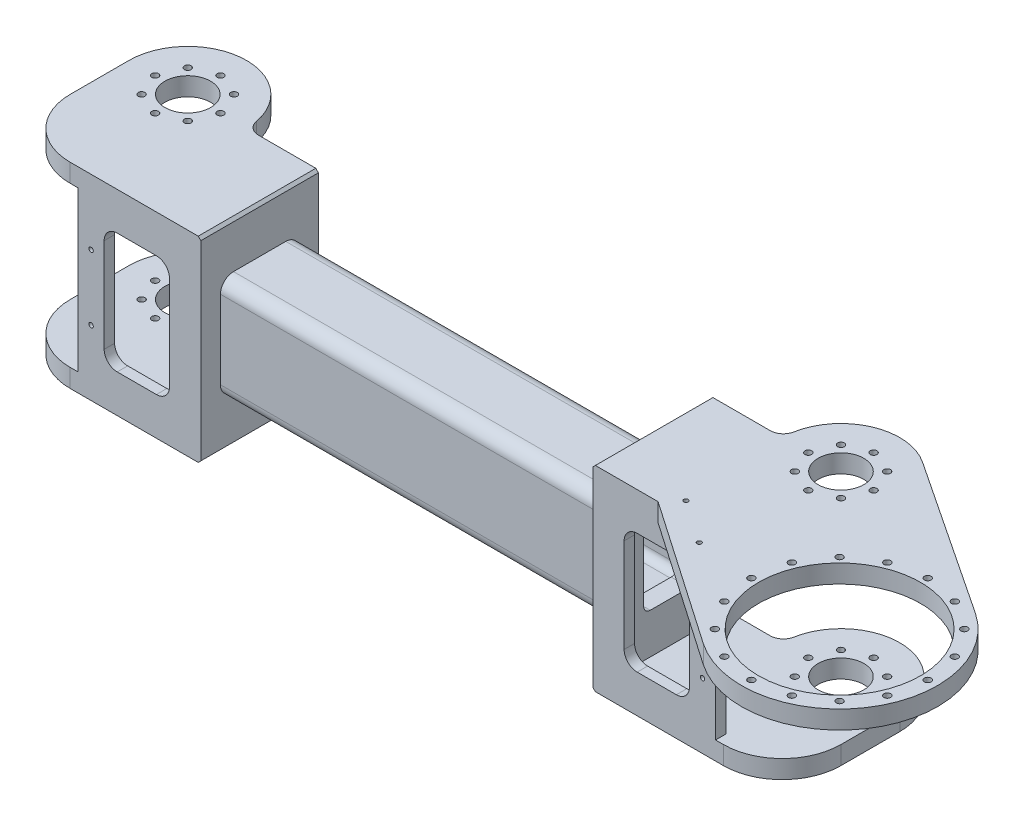
SolidWorks part; units mm, degrees
material "Q235"
ref_plane "Front" through (0, 0, 0) normal (0, 0, 1) x (1, 0, 0)
ref_plane "Top" through (0, 0, 0) normal (0, 1, 0) x (1, 0, 0)
ref_plane "Right" through (0, 0, 0) normal (1, 0, 0) x (0, 0, -1)
sketch "草图1" plane through (0, 0, 0) normal (0, 1, 0) x (1, 0, 0)
  line L0 (-45.9167, 45) -> (0, 45)
  line L1 (0, 45) -> (0, -45)
  line L2 (0, -45) -> (-100, -45)
  line L3 (-145, 0) -> (-145, 45)
  line L4 (0, 0) -> (-100, 0) construction
  line L5 (-100, 0) -> (-100, 45) construction
  arc A0 (-145, 45) -> (-55.7501, 53.1818) centre (-100, 45) cw
  arc A1 (-45.9167, 45) -> (-55.7501, 53.1818) centre (-45.9167, 55) cw
  arc A2 (-145, 0) -> (-100, -45) centre (-100, 0) ccw
  point P5 (0, 0)
  dimension "D2" = 100
  dimension "D5" = 10
  dimension "D6" = 45
  dimension "D1" = 90
  dimension "D3" = 45
  dimension "D4" = 145
extrude "凸台-拉伸1" add sketch "草图1" along normal mid plane 150
sketch "草图2" plane through (0, 0, 45) normal (0, 0, 1) x (1, 0, 0)
  line L1 (-314, 61) -> (-14, 61)
  line L2 (-314, 61) -> (-314, -61)
  line L3 (-314, -61) -> (-14, -61)
  line L4 (-14, 61) -> (-14, -61)
  line L6 (0, 75) -> (0, -75) construction
  point P4 (0, 0)
  dimension "D1" = 122
  dimension "D2" = 61
  dimension "D3" = 14
  dimension "D4" = 300
extrude "切除-拉伸1" cut sketch "草图2" against normal blind 200
sketch "草图3" plane through (0, 75, 0) normal (0, 1, 0) x (1, 0, 0)
  line L0 (0, 0) -> (-100, 0) construction
  line L1 (0, -45) -> (0, 45) construction
  line L2 (-100, 0) -> (-100, 45) construction
  circle A0 centre (-100, 45) radius 17.5
  dimension "D1" = 35
  dimension "D2" = 100
  dimension "D3" = 45
extrude "切除-拉伸2" cut sketch "草图3" against normal blind 240
sketch "草图4" plane through (0, -75, 0) normal (0, -1, 0) x (1, 0, 0)
  circle A0 centre (-100, -45) radius 25 construction
  circle A1 centre (-100, -20) radius 2.55
  circle A2 centre (-117.6777, -27.3223) radius 2.55
  circle A3 centre (-125, -45) radius 2.55
  circle A4 centre (-117.6777, -62.6777) radius 2.55
  circle A5 centre (-100, -70) radius 2.55
  circle A6 centre (-82.3223, -62.6777) radius 2.55
  circle A7 centre (-75, -45) radius 2.55
  circle A8 centre (-82.3223, -27.3223) radius 2.55
  point P22 (-100, -45)
  dimension "D1" = 50
  dimension "D2" = 5.1
  dimension "D3" = 8
extrude "切除-拉伸3" cut sketch "草图4" against normal blind 240
sketch "草图8" plane through (0, 0, 0) normal (0, 1, 0) x (1, 0, 0)
  line L0 (0, 0) -> (300, 0) construction
  line L1 (345.9167, 45) -> (300, 45)
  line L2 (300, 45) -> (300, -45)
  line L3 (300, -45) -> (400, -45)
  line L4 (300, 0) -> (400, 0) construction
  line L5 (400, 0) -> (506.066, -106.066) construction
  line L6 (445, 0) -> (445, 45)
  line L7 (400, 0) -> (400, 45) construction
  arc A0 (400, -45) -> (445, 0) centre (400, 0) ccw
  circle A1 centre (506.066, -106.066) radius 100 construction
  arc A2 (355.7501, 53.1818) -> (445, 45) centre (400, 45) cw
  arc A3 (355.7501, 53.1818) -> (345.9167, 45) centre (345.9167, 55) cw
  dimension "D1" = 90
  dimension "D5" = 200
  dimension "D7" = 45
  dimension "D8" = 10
  dimension "D2" = 300
  dimension "D3" = 100
  dimension "D4" = 150
  dimension "D6" = 135
extrude "凸台-拉伸4" add sketch "草图8" along normal mid plane 150 separate body
sketch "草图9" plane through (0, 0, 0) normal (1, 0, 0) x (0, 0, -1)
  line L0 (30, 40) -> (-30, -40) construction
  line L1 (-20, 40) -> (20, 40)
  line L2 (-30, 30) -> (-30, -30)
  line L3 (-20, -40) -> (20, -40)
  line L4 (30, 30) -> (30, -30)
  line L5 (0, 0) -> (-30, 0) construction
  line L6 (26, 30) -> (26, -30)
  line L7 (-20, -36) -> (20, -36)
  line L8 (-26, 30) -> (-26, -30)
  line L9 (-20, 36) -> (20, 36)
  arc A0 (20, 40) -> (30, 30) centre (20, 30) cw
  arc A1 (30, -30) -> (20, -40) centre (20, -30) cw
  arc A2 (-20, -40) -> (-30, -30) centre (-20, -30) cw
  arc A3 (-30, 30) -> (-20, 40) centre (-20, 30) cw
  arc A4 (26, -30) -> (20, -36) centre (20, -30) cw
  arc A5 (-20, -36) -> (-26, -30) centre (-20, -30) cw
  arc A6 (-26, 30) -> (-20, 36) centre (-20, 30) cw
  arc A7 (20, 36) -> (26, 30) centre (20, 30) cw
  dimension "D3" = 10
  dimension "D1" = 60
  dimension "D2" = 80
  dimension "D4" = 4
extrude "凸台-拉伸5" add sketch "草图9" along normal up to surface (300 mm away) up to face at (300, 0, 0)
sketch "草图10" plane through (0, 0, 45) normal (0, 0, 1) x (1, 0, 0)
  line L0 (300, 75) -> (300, -75) construction
  line L1 (314, 61) -> (514, 61)
  line L2 (314, 61) -> (314, -61)
  line L3 (314, -61) -> (514, -61)
  line L4 (514, 61) -> (514, -61)
  line L5 (0, 0) -> (381.7242, 0) construction
  dimension "D1" = 122
  dimension "D2" = 14
  dimension "D3" = 61
  dimension "D4" = 200
extrude "切除-拉伸4" cut sketch "草图10" against normal blind 200
sketch "草图11" plane through (0, 75, 0) normal (0, 1, 0) x (1, 0, 0)
  line L0 (300, 0) -> (400, 0) construction
  line L1 (300, 45) -> (300, -45) construction
  line L2 (400, 0) -> (400, 45) construction
  circle A0 centre (400, 45) radius 17.5
  dimension "D1" = 35
  dimension "D2" = 100
  dimension "D3" = 45
extrude "切除-拉伸5" cut sketch "草图11" against normal up to surface (150 mm away) up to face at (372.3141, -75, -18.2579)
sketch "草图12" plane through (0, 75, 0) normal (0, 1, 0) x (1, 0, 0)
  circle A0 centre (400, 45) radius 25 construction
  circle A1 centre (375, 45) radius 2.55
  circle A2 centre (382.3223, 27.3223) radius 2.55
  circle A3 centre (400, 20) radius 2.55
  circle A4 centre (417.6777, 27.3223) radius 2.55
  circle A5 centre (425, 45) radius 2.55
  circle A6 centre (417.6777, 62.6777) radius 2.55
  circle A7 centre (400, 70) radius 2.55
  circle A8 centre (382.3223, 62.6777) radius 2.55
  point P21 (400, 45)
  dimension "D1" = 50
  dimension "D2" = 5.1
  dimension "D3" = 8
extrude "切除-拉伸6" cut sketch "草图12" against normal up to surface (150 mm away) up to face at (400, -75, -27.5)
sketch "草图13" plane through (0, 75, 0) normal (0, 1, 0) x (1, 0, 0)
  line L0 (0, 0) -> (400, 0) construction
  line L1 (400, 0) -> (503.923, -60) construction
  line L2 (445, 0) -> (445, 45) construction
  line L3 (400, -45) -> (350, -45)
  line L4 (300, -45) -> (400, -45) construction
  line L5 (445, 0) -> (445, 45)
  line L6 (424.8888, 82.4906) -> (545.4043, 2.4844)
  line L7 (461.3609, -121.7532) -> (350, -45)
  line L10 (300, 45) -> (300, -45) construction
  arc A0 (400, -45) -> (445, 0) centre (400, 0) ccw construction
  arc A1 (400, -45) -> (445, 0) centre (400, 0) ccw
  arc A2 (545.4043, 2.4844) -> (461.3609, -121.7532) centre (503.923, -60) cw
  arc A3 (445, 45) -> (355.7501, 53.1818) centre (400, 45) ccw construction
  arc A4 (445, 45) -> (424.8888, 82.4906) centre (400, 45) ccw
  dimension "D1" = 30
  dimension "D2" = 75
  dimension "D3" = 120
  dimension "D4" = 50
extrude "凸台-拉伸6" add sketch "草图13" against normal up to surface (14 mm away) up to face at (382.3223, 61, -24.7723)
sketch "草图14" plane through (0, 75, 0) normal (0, 1, 0) x (1, 0, 0)
  circle A0 centre (503.923, -60) radius 62
  dimension "D1" = 124
extrude "切除-拉伸7" cut sketch "草图14" against normal blind 14
sketch "草图15" plane through (0, 75, 0) normal (0, 1, 0) x (1, 0, 0)
  circle A0 centre (503.923, -60) radius 67.5 construction
  circle A1 centre (503.923, -127.5) radius 2.55
  circle A2 centre (529.7542, -122.3619) radius 2.55
  circle A3 centre (551.6528, -107.7297) radius 2.55
  circle A4 centre (566.2849, -85.8311) radius 2.55
  circle A5 centre (571.423, -60) radius 2.55
  circle A6 centre (566.2849, -34.1689) radius 2.55
  circle A7 centre (551.6528, -12.2703) radius 2.55
  circle A8 centre (529.7542, 2.3619) radius 2.55
  circle A9 centre (503.923, 7.5) radius 2.55
  circle A10 centre (478.0919, 2.3619) radius 2.55
  circle A11 centre (456.1933, -12.2703) radius 2.55
  circle A12 centre (441.5612, -34.1689) radius 2.55
  circle A13 centre (436.423, -60) radius 2.55
  circle A14 centre (441.5612, -85.8311) radius 2.55
  circle A15 centre (456.1933, -107.7297) radius 2.55
  circle A16 centre (478.0919, -122.3619) radius 2.55
  point P38 (503.923, -60)
  dimension "D1" = 135
  dimension "D2" = 5.1
  dimension "D3" = 16
extrude "切除-拉伸8" cut sketch "草图15" against normal blind 14
sketch "草图16" plane through (-14, 0, 0) normal (-1, 0, 0) x (0, 0, 1)
  line L0 (20, 30) -> (-20, -30) construction
  line L1 (-15, 30) -> (15, 30)
  line L2 (-20, 25) -> (-20, -25)
  line L3 (-15, -30) -> (15, -30)
  line L4 (20, 25) -> (20, -25)
  line L5 (0, 0) -> (0, -20.2872) construction
  line L6 (0, 0) -> (20, 0) construction
  arc A0 (-20, -25) -> (-15, -30) centre (-15, -25) ccw
  arc A1 (15, -30) -> (20, -25) centre (15, -25) ccw
  arc A2 (20, 25) -> (15, 30) centre (15, 25) ccw
  arc A3 (-20, 25) -> (-15, 30) centre (-15, 25) cw
  dimension "D3" = 5
  dimension "D1" = 40
  dimension "D2" = 60
extrude "切除-拉伸9" cut sketch "草图16" against normal up to surface (328 mm away) up to face at (314, 0, 0)
sketch "草图17" plane through (0, 75, 0) normal (0, 1, 0) x (1, 0, 0)
  line L0 (360, -33.6746) -> (392.9351, -56.3745) construction
  line L1 (300, 45) -> (300, -45) construction
  line L2 (350, -45) -> (461.3609, -121.7532) construction
  circle A0 centre (360, -33.6746) radius 1.7
  circle A1 centre (392.9351, -56.3745) radius 1.7
  dimension "D1" = 3.4
  dimension "D2" = 3.4
  dimension "D5" = 60
  dimension "D3" = 40
  dimension "D4" = 15
extrude "切除-拉伸10" cut sketch "草图17" against normal blind 14
sketch "草图18" plane through (314, 0, 0) normal (1, 0, 0) x (0, 0, -1)
  line L0 (45, -61) -> (-45, -61) construction
  line L1 (-45, 61) -> (-37, 61)
  line L2 (-45, 61) -> (-45, -61)
  line L3 (-45, -61) -> (-37, -61)
  line L4 (-37, 61) -> (-37, -61)
  dimension "D1" = 8
extrude "凸台-拉伸7" add sketch "草图18" along normal blind 80
sketch "草图19" plane through (0, 0, 37) normal (0, 0, -1) x (-1, 0, 0)
  line L0 (-394, 61) -> (-314, 61) construction
  line L1 (-364, 46) -> (-334, 46)
  line L2 (-374, 36) -> (-374, -36)
  line L3 (-364, -46) -> (-334, -46)
  line L4 (-324, 36) -> (-324, -36)
  line L5 (-394, -61) -> (-394, 61) construction
  line L6 (-394, -61) -> (-314, -61) construction
  line L7 (-314, -61) -> (-314, 61) construction
  arc A0 (-334, 46) -> (-324, 36) centre (-334, 36) cw
  arc A1 (-374, -36) -> (-364, -46) centre (-364, -36) ccw
  arc A2 (-334, -46) -> (-324, -36) centre (-334, -36) ccw
  arc A3 (-364, 46) -> (-374, 36) centre (-364, 36) ccw
  dimension "D5" = 10
  dimension "D1" = 15
  dimension "D2" = 20
  dimension "D3" = 15
  dimension "D4" = 10
extrude "切除-拉伸11" cut sketch "草图19" against normal blind 8
sketch "草图20" plane through (-14, 0, 0) normal (-1, 0, 0) x (0, 0, 1)
  line L0 (-45, -61) -> (45, -61) construction
  line L1 (45, 61) -> (37, 61)
  line L2 (45, 61) -> (45, -61)
  line L3 (45, -61) -> (37, -61)
  line L4 (37, 61) -> (37, -61)
  dimension "D1" = 8
extrude "凸台-拉伸8" add sketch "草图20" along normal blind 80
sketch "草图21" plane through (0, 0, 37) normal (0, 0, -1) x (-1, 0, 0)
  line L0 (94, 61) -> (94, -61) construction
  line L1 (34, 46) -> (64, 46)
  line L2 (24, 36) -> (24, -36)
  line L3 (34, -46) -> (64, -46)
  line L4 (74, 36) -> (74, -36)
  line L5 (94, 61) -> (14, 61) construction
  line L6 (14, 61) -> (14, -61) construction
  line L7 (94, -61) -> (14, -61) construction
  arc A0 (64, 46) -> (74, 36) centre (64, 36) cw
  arc A1 (24, -36) -> (34, -46) centre (34, -36) ccw
  arc A2 (64, -46) -> (74, -36) centre (64, -36) ccw
  arc A3 (34, 46) -> (24, 36) centre (34, 36) ccw
  dimension "D5" = 10
  dimension "D1" = 20
  dimension "D2" = 15
  dimension "D3" = 10
  dimension "D4" = 15
extrude "切除-拉伸12" cut sketch "草图21" against normal blind 8
sketch "草图22" plane through (0, 0, 37) normal (0, 0, -1) x (-1, 0, 0)
  line L0 (84, 25) -> (84, -25) construction
  line L1 (0, 0) -> (60.4163, 0) construction
  line L2 (94, 61) -> (94, -61) construction
  circle A0 centre (84, 25) radius 1.7
  circle A1 centre (84, -25) radius 1.7
  dimension "D1" = 3.4
  dimension "D2" = 3.4
  dimension "D4" = 25
  dimension "D3" = 50
  dimension "D5" = 10
extrude "切除-拉伸13" cut sketch "草图22" against normal blind 10
chamfer "倒角1" distance 2 angle 45 4 edges at (0, -75, 0) (0, 75, 0) (300, -75, 0) (300, 75, 0)
sketch "草图23" plane through (0, 0, 37) normal (0, 0, -1) x (-1, 0, 0)
  line L0 (-384, 25) -> (-384, -25) construction
  line L1 (0, 0) -> (-270.3578, 0) construction
  line L2 (-394, -61) -> (-394, 61) construction
  circle A0 centre (-384, 25) radius 1.7
  circle A1 centre (-384, -25) radius 1.7
  dimension "D1" = 3.4
  dimension "D2" = 3.4
  dimension "D4" = 25
  dimension "D3" = 50
  dimension "D5" = 10
extrude "切除-拉伸14" cut sketch "草图23" against normal blind 10
